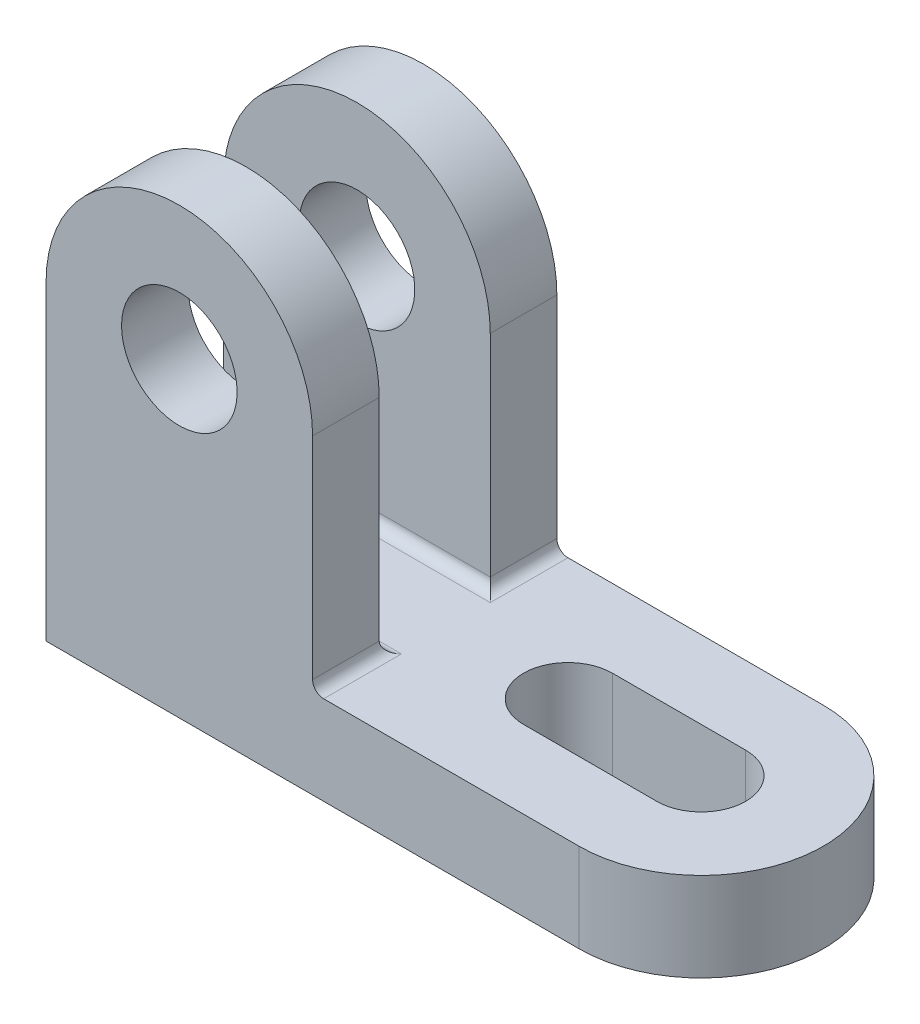
SolidWorks part; units mm, degrees
ref_plane "Front Plane" through (0, 0, 0) normal (0, 0, 1) x (1, 0, 0)
ref_plane "Top Plane" through (0, 0, 0) normal (0, 1, 0) x (1, 0, 0)
ref_plane "Right Plane" through (0, 0, 0) normal (1, 0, 0) x (0, 0, -1)
sketch "Sketch4" plane through (0, 0, 0) normal (0, 1, 0) x (1, 0, 0)
  line L1 (-59, -22) -> (37, -22)
  line L2 (-59, -22) -> (-59, 22)
  line L3 (-59, 22) -> (37, 22)
  line L5 (-59, -22) -> (59, 22) construction
  line L6 (-59, 22) -> (59, -22) construction
  arc A0 (37, -22) -> (37, 22) centre (37, 0) ccw
  point P0 (0, 0)
  dimension "D1" = 118
  dimension "D2" = 44
extrude "Boss-Extrude1" add sketch "Sketch4" along normal blind 16
sketch "Sketch6" plane through (0, 16, 0) normal (0, 1, 0) x (1, 0, 0)
  line L0 (37, 0) -> (13, 0) construction
  line L1 (37, -8) -> (13, -8)
  line L2 (37, 8) -> (13, 8)
  arc A0 (37, -8) -> (37, 8) centre (37, 0) ccw
  arc A1 (13, 8) -> (13, -8) centre (13, 0) ccw
  point P4 (25, 0)
  dimension "D1" = 16
  dimension "D2" = 24
extrude "Cut-Extrude2" cut sketch "Sketch6" against normal blind 16
sketch "Sketch9" plane through (0, 0, -22) normal (0, 0, -1) x (-1, 0, 0)
  line L1 (59, 16) -> (11, 16)
  line L2 (59, 16) -> (59, 56)
  line L3 (59, 56) -> (11, 56)
  line L4 (11, 16) -> (11, 56)
  circle A0 centre (35, 56) radius 24
  circle A1 centre (35, 56) radius 10.4088
  line M5 (59, 16) -> (-37, 16)
  dimension "D3" = 20.8177
  dimension "D1" = 40
  dimension "D2" = 48
extrude "Boss-Extrude2" add sketch "Sketch9" against normal blind 12 contours A0 L4 L2 M5 | A1 L3 A0 | A1 L3 A0
mirror "Mirror5" about plane through (0, 0, 0) normal (0, 0, 1) of "Boss-Extrude2"
fillet "Fillet3" radius 2 4 edges at (-11, 16, -16) (-35, 16, -10) (-11, 16, 16) (-35, 16, 10)
